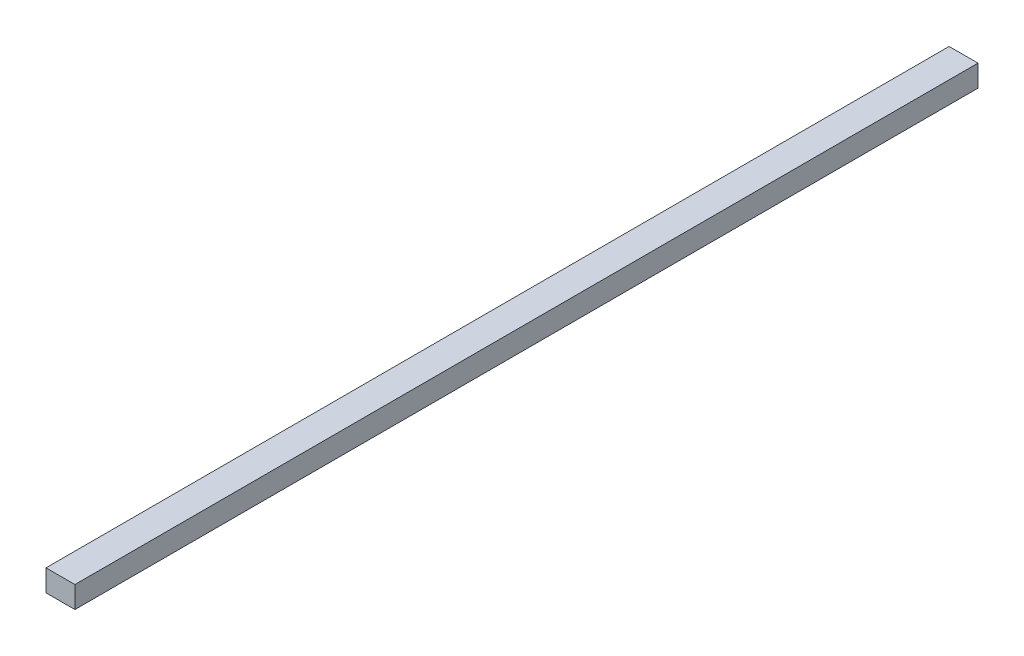
SolidWorks part; units mm, degrees
ref_plane "Front Plane" through (0, 0, 0) normal (0, 0, 1) x (1, 0, 0)
ref_plane "Top Plane" through (0, 0, 0) normal (0, 1, 0) x (1, 0, 0)
ref_plane "Right Plane" through (0, 0, 0) normal (1, 0, 0) x (0, 0, -1)
other "Configuration Table"
sketch "Sketch1" plane through (0, 0, 0) normal (0, 0, 1) x (1, 0, 0)
  line L1 (290, 1176) -> (306, 1176)
  line L2 (290, 1176) -> (290, 1188)
  line L3 (290, 1188) -> (306, 1188)
  line L4 (306, 1176) -> (306, 1188)
extrude "PRESS_uc_catal_lama_1_1" add sketch "Sketch1" against normal blind 500 from offset 50 separate body
